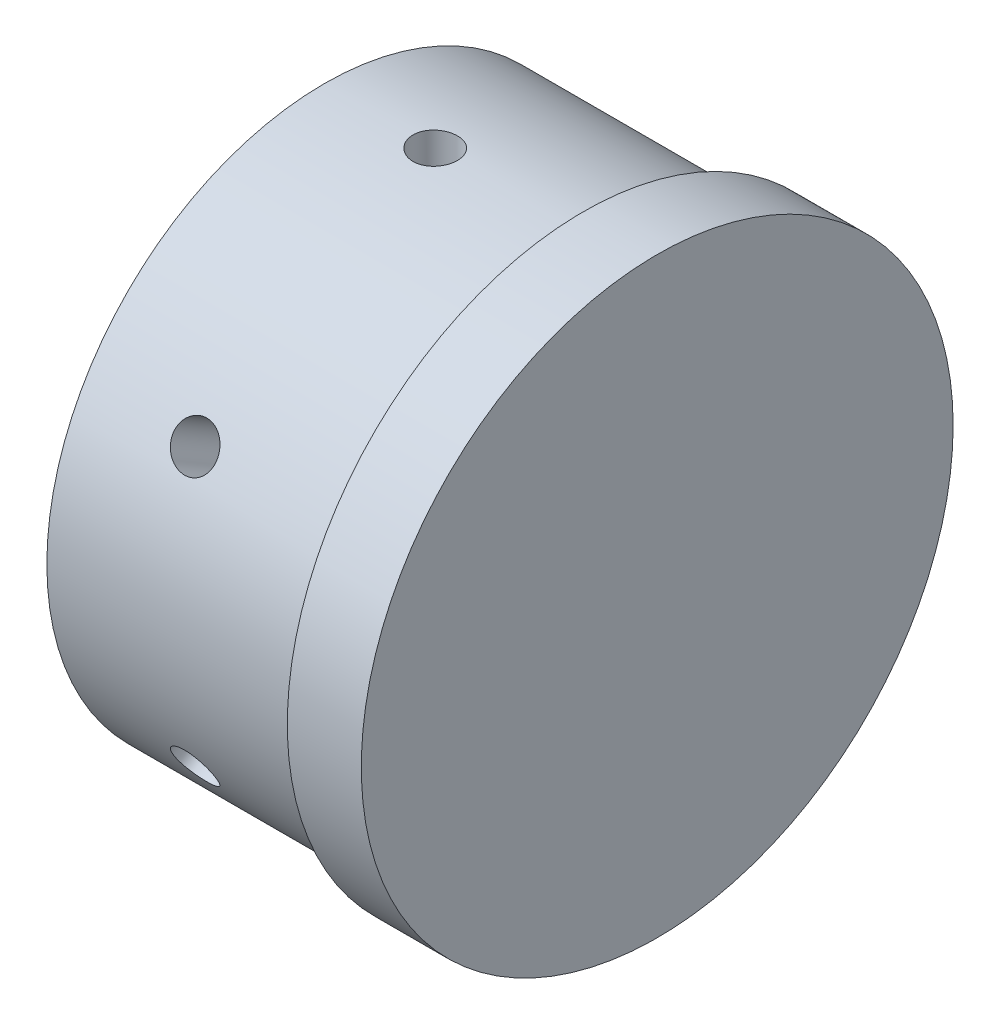
SolidWorks part; units mm, degrees
ref_plane "Front Plane" through (0, 0, 0) normal (0, 0, 1) x (1, 0, 0)
ref_plane "Top Plane" through (0, 0, 0) normal (0, 1, 0) x (1, 0, 0)
ref_plane "Right Plane" through (0, 0, 0) normal (1, 0, 0) x (0, 0, -1)
sketch "Sketch1" plane through (0, 0, 0) normal (1, 0, 0) x (0, 0, -1)
  circle A0 centre (0, 0) radius 37.5
  dimension "D1" = 75
extrude "Boss-Extrude1" add sketch "Sketch1" along normal blind 35
sketch "Sketch2" plane through (35, 0, 0) normal (1, 0, 0) x (0, 0, -1)
  circle A0 centre (0, 0) radius 40
  dimension "D1" = 80
extrude "Boss-Extrude2" add sketch "Sketch2" along normal blind 10
ref_plane "Bolts" through (0, 37.5, 0) normal (0, 1, 0) x (1, 0, 0)
sketch "Sketch3" plane through (0, 37.5, 0) normal (0, 1, 0) x (1, 0, 0)
  line L0 (35, 0) -> (15, 0) construction
  line L1 (35, 40) -> (35, -40) construction
  circle A0 centre (15, 0) radius 3
  dimension "D2" = 6
  dimension "D1" = 20
extrude "Cut-Extrude1" cut sketch "Sketch3" against normal blind 10
pattern_circular "CirPattern1" count 6 over 360 about axis through (0, 0, 0) along (1, 0, 0) of "Cut-Extrude1"
